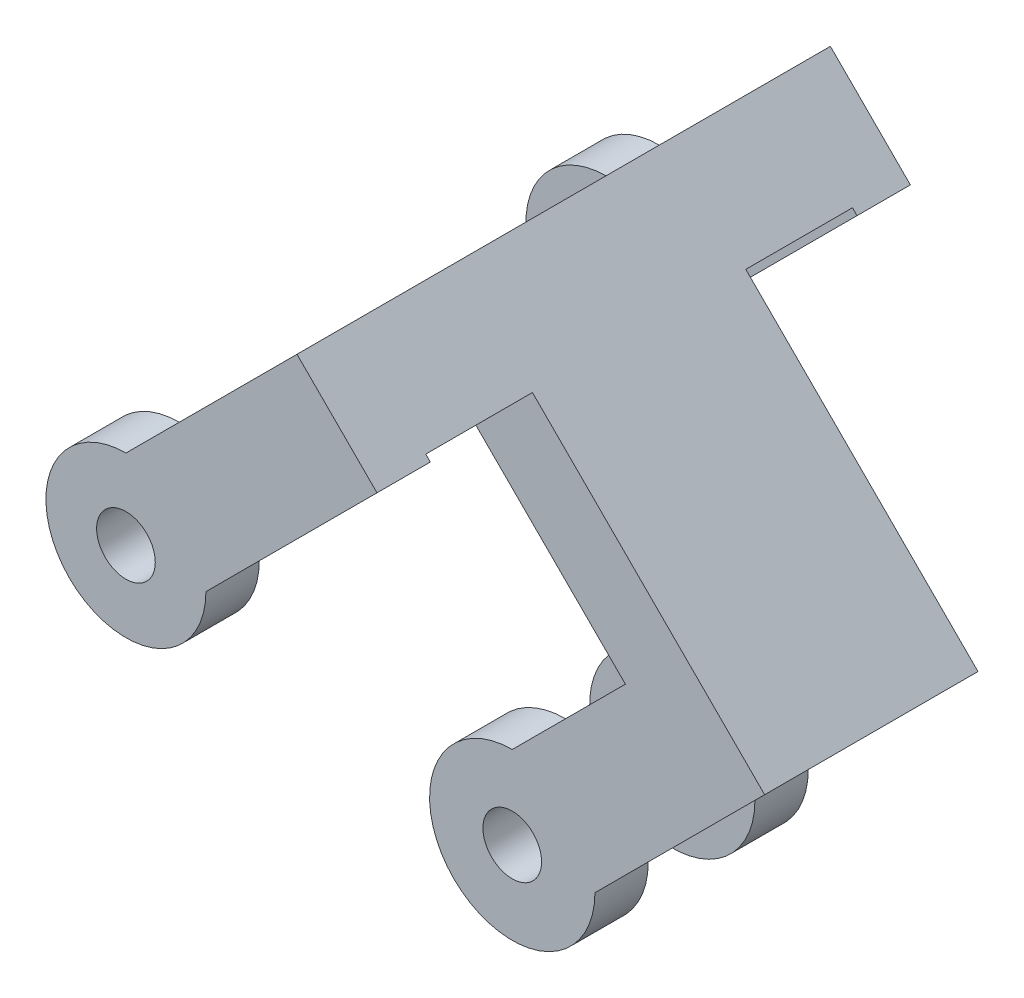
SolidWorks part; units mm, degrees
ref_plane "Front Plane" through (0, 0, 0) normal (0, 0, 1) x (1, 0, 0)
ref_plane "Top Plane" through (0, 0, 0) normal (0, 1, 0) x (1, 0, 0)
ref_plane "Right Plane" through (0, 0, 0) normal (1, 0, 0) x (0, 0, -1)
sketch "Sketch1" plane through (0, 0, 0) normal (0, 0, 1) x (1, 0, 0)
  circle A0 centre (-68.7868, 328.7868) radius 2.75 construction
  circle A1 centre (-68.7868, 328.7868) radius 2.75
  circle A2 centre (-68.7868, 328.7868) radius 7.75
  dimension "D1" = 5
extrude "Boss-Extrude1" add sketch "Sketch1" along normal blind 5
sketch "Sketch2" plane through (0, 0, -10) normal (0, 0, -1) x (-1, 0, 0)
  circle A0 centre (68.7868, 328.7868) radius 2.75 construction
  circle A1 centre (68.7868, 328.7868) radius 7.75
  circle A2 centre (68.7868, 328.7868) radius 7.75
  circle A3 centre (68.7868, 328.7868) radius 2.75
  dimension "D1" = 0
extrude "Boss-Extrude2" add sketch "Sketch2" along normal blind 5 separate body
sketch "Sketch3" plane through (0, 0, -15) normal (0, 0, -1) x (-1, 0, 0)
  line L0 (61.0368, 328.7868) -> (43.3591, 346.4645)
  line L1 (43.3591, 346.4645) -> (72.1973, 375.3027)
  line L2 (90, 357.5) -> (72.1973, 375.3027)
  line L3 (82.5, 350) -> (69.6471, 362.8529)
  line L4 (68.7868, 336.5368) -> (56.0589, 349.2647)
  line L5 (56.0589, 349.2647) -> (69.6471, 362.8529)
  circle A0 centre (68.7868, 328.7868) radius 7.75 construction
  circle A1 centre (90, 350) radius 2.75
  circle A2 centre (90, 350) radius 7.5
  circle M6 centre (68.7868, 328.7868) radius 7.75
  dimension "D3" = 15
  dimension "D1" = 25
  dimension "D2" = 18
extrude "Boss-Extrude4" add sketch "Sketch3" against normal blind 5 contours A2 A1 | A2 L2 L1 L0 L4 L5 L3 M6
sketch "Sketch4" plane through (0, 0, 0) normal (0, 0, 1) x (1, 0, 0)
  line L6 (-61.0368, 328.7868) -> (-43.3591, 346.4645)
  line L7 (-43.3591, 346.4645) -> (-72.1973, 375.3027)
  line L8 (-72.1973, 375.3027) -> (-90, 357.5)
  line L9 (-82.5, 350) -> (-69.6471, 362.8529)
  line L10 (-69.6471, 362.8529) -> (-56.0589, 349.2647)
  line L11 (-56.0589, 349.2647) -> (-68.7868, 336.5368)
  line L12 (-61.0368, 328.7868) -> (-43.3591, 346.4645)
  line L13 (-43.3591, 346.4645) -> (-72.1973, 375.3027)
  line L14 (-72.1973, 375.3027) -> (-90, 357.5)
  line L15 (-82.5, 350) -> (-69.6471, 362.8529)
  line L16 (-69.6471, 362.8529) -> (-56.0589, 349.2647)
  line L17 (-56.0589, 349.2647) -> (-68.7868, 336.5368)
  arc A2 (-68.7868, 336.5368) -> (-61.0368, 328.7868) centre (-68.7868, 328.7868) ccw
  arc A3 (-90, 357.5) -> (-82.5, 350) centre (-90, 350) ccw
  arc A4 (-68.7868, 336.5368) -> (-61.0368, 328.7868) centre (-68.7868, 328.7868) ccw
  arc A5 (-90, 357.5) -> (-82.5, 350) centre (-90, 350) ccw
  dimension "D1" = 0
extrude "Boss-Extrude5" add sketch "Sketch4" along normal blind 5
sketch "Sketch6" plane through (151.5527, 151.5527, 0) normal (0.7071, 0.7071, 0) x (0, 0, -1)
  line L1 (-5, 316.4303) -> (15, 316.4303)
  line L2 (-5, 316.4303) -> (-5, 275.6469)
  line L3 (-5, 275.6469) -> (15, 275.6469)
  line L4 (15, 316.4303) -> (15, 275.6469)
extrude "Boss-Extrude6" add sketch "Sketch6" against normal blind 10
sketch "Sketch7" plane through (0, 0, 5) normal (0, 0, 1) x (1, 0, 0)
  circle A0 centre (-68.7868, 328.7868) radius 2.75 construction
  circle A1 centre (-90, 350) radius 2.75 construction
  circle A2 centre (-68.7868, 328.7868) radius 2.75
  circle A3 centre (-90, 350) radius 2.75
extrude "Cut-Extrude1" cut sketch "Sketch7" against normal blind 10
sketch "Sketch9" plane through (0, 0, 5) normal (0, 0, 1) x (1, 0, 0)
  line L0 (-71.7684, 360.7316) -> (-64.6973, 367.8027)
  line L1 (-71.7684, 360.7316) -> (-79.2684, 368.2316)
  line L6 (-72.1973, 375.3027) -> (-90, 357.5)
  line L7 (-82.5, 350) -> (-71.7684, 360.7316)
  line L8 (-71.7684, 360.7316) -> (-58.1802, 347.1434)
  line L9 (-58.1802, 347.1434) -> (-68.7868, 336.5368)
  line L10 (-61.0368, 328.7868) -> (-43.3591, 346.4645)
  line L11 (-43.3591, 346.4645) -> (-72.1973, 375.3027)
  line L12 (-72.1973, 375.3027) -> (-90, 357.5)
  line L13 (-82.5, 350) -> (-71.7684, 360.7316)
  line L14 (-71.7684, 360.7316) -> (-58.1802, 347.1434)
  line L15 (-58.1802, 347.1434) -> (-68.7868, 336.5368)
  line L16 (-61.0368, 328.7868) -> (-43.3591, 346.4645)
  line L17 (-43.3591, 346.4645) -> (-72.1973, 375.3027)
  arc A2 (-90, 357.5) -> (-82.5, 350) centre (-90, 350) ccw
  arc A3 (-68.7868, 336.5368) -> (-61.0368, 328.7868) centre (-68.7868, 328.7868) ccw
  arc A4 (-90, 357.5) -> (-82.5, 350) centre (-90, 350) ccw
  arc A5 (-68.7868, 336.5368) -> (-61.0368, 328.7868) centre (-68.7868, 328.7868) ccw
  circle M10 centre (-90, 350) radius 2.75
  line M11 (-72.1973, 375.3027) -> (-90, 357.5)
  arc M12 (-90, 357.5) -> (-82.5, 350) centre (-90, 350) ccw
  line M13 (-82.5, 350) -> (-71.7684, 360.7316)
  dimension "D1" = 0
extrude "Cut-Extrude2" cut sketch "Sketch9" against normal through all contours L1 M13 M11 M12 M10
sketch "Sketch10" plane through (0, 0, 5) normal (0, 0, 1) x (1, 0, 0)
  line L0 (-65.1263, 368.2316) -> (-72.1973, 361.1605)
  line L5 (-72.1973, 375.3027) -> (-79.2684, 368.2316)
  line L6 (-79.2684, 368.2316) -> (-58.1802, 347.1434)
  line L7 (-58.1802, 347.1434) -> (-68.7868, 336.5368)
  line L8 (-61.0368, 328.7868) -> (-43.3591, 346.4645)
  line L9 (-43.3591, 346.4645) -> (-72.1973, 375.3027)
  line L10 (-72.1973, 375.3027) -> (-79.2684, 368.2316)
  line L11 (-79.2684, 368.2316) -> (-58.1802, 347.1434)
  line L12 (-58.1802, 347.1434) -> (-68.7868, 336.5368)
  line L13 (-61.0368, 328.7868) -> (-43.3591, 346.4645)
  line L14 (-43.3591, 346.4645) -> (-72.1973, 375.3027)
  arc A1 (-68.7868, 336.5368) -> (-61.0368, 328.7868) centre (-68.7868, 328.7868) ccw
  arc A2 (-68.7868, 336.5368) -> (-61.0368, 328.7868) centre (-68.7868, 328.7868) ccw
  line M7 (-72.1973, 375.3027) -> (-79.2684, 368.2316)
  line M8 (-79.2684, 368.2316) -> (-58.1802, 347.1434)
  line M12 (-43.3591, 346.4645) -> (-72.1973, 375.3027)
  dimension "D1" = 0
  dimension "D2" = 10
extrude "Boss-Extrude7" add sketch "Sketch10" along normal blind 15 contours L0 M12 M7 M8
sketch "Sketch11" plane through (0, 0, -15) normal (0, 0, -1) x (-1, 0, 0)
  line L4 (65.1263, 368.2316) -> (72.1973, 361.1605)
  line L5 (72.1973, 375.3027) -> (65.1263, 368.2316)
  line L6 (79.2684, 368.2316) -> (72.1973, 375.3027)
  line L7 (72.1973, 361.1605) -> (79.2684, 368.2316)
  line L8 (65.1263, 368.2316) -> (72.1973, 361.1605)
  line L9 (72.1973, 375.3027) -> (65.1263, 368.2316)
  line L10 (79.2684, 368.2316) -> (72.1973, 375.3027)
  line L11 (72.1973, 361.1605) -> (79.2684, 368.2316)
  dimension "D1" = 0
extrude "Boss-Extrude8" add sketch "Sketch11" along normal blind 15
sketch "Sketch12" plane through (0, 0, 20) normal (0, 0, 1) x (1, 0, 0)
  line L0 (-58.1802, 347.1434) -> (-51.1091, 354.2145)
  line L1 (-90, 357.5) -> (-79.2684, 368.2316)
  line L2 (-79.2684, 368.2316) -> (-50.4302, 339.3934)
  line L3 (-82.5, 350) -> (-64.2684, 368.2316)
  line L4 (-65.1263, 368.2316) -> (-64.6973, 367.8027)
  line L5 (-43.3591, 346.4645) -> (-65.1263, 368.2316)
  line L6 (-65.1263, 368.2316) -> (-72.1973, 361.1605)
  line L7 (-72.1973, 361.1605) -> (-58.1802, 347.1434)
  line L8 (-58.1802, 347.1434) -> (-68.7868, 336.5368)
  line L9 (-61.0368, 328.7868) -> (-43.3591, 346.4645)
  line L10 (-43.3591, 346.4645) -> (-51.1091, 354.2145)
  line L13 (-58.1802, 347.1434) -> (-68.7868, 336.5368)
  line L14 (-61.0368, 328.7868) -> (-43.3591, 346.4645)
  line L15 (-65.1263, 368.2316) -> (-43.3591, 346.4645) construction
  line L20 (-72.1973, 361.1605) -> (-65.1263, 368.2316)
  line L21 (-65.1263, 368.2316) -> (-72.1973, 375.3027)
  line L22 (-72.1973, 375.3027) -> (-79.2684, 368.2316)
  line L23 (-79.2684, 368.2316) -> (-72.1973, 361.1605)
  line L24 (-72.1973, 361.1605) -> (-65.1263, 368.2316)
  line L25 (-65.1263, 368.2316) -> (-72.1973, 375.3027)
  line L26 (-72.1973, 375.3027) -> (-79.2684, 368.2316)
  line L27 (-79.2684, 368.2316) -> (-72.1973, 361.1605)
  circle A0 centre (-68.7868, 328.7868) radius 2.75 construction
  arc A1 (-68.7868, 336.5368) -> (-61.0368, 328.7868) centre (-68.7868, 328.7868) ccw
  arc A2 (-68.7868, 336.5368) -> (-61.0368, 328.7868) centre (-68.7868, 328.7868) ccw
  circle A3 centre (-68.7868, 328.7868) radius 2.75
  circle A4 centre (-90, 350) radius 2.75
  circle A5 centre (-90, 350) radius 7.5
  line M14 (-72.1973, 361.1605) -> (-65.1263, 368.2316)
  line M17 (-79.2684, 368.2316) -> (-72.1973, 361.1605)
  dimension "D2" = 15
  dimension "D1" = 0
  dimension "D3" = 0
extrude "Boss-Extrude9" add sketch "Sketch12" against normal blind 5 contours A5 L3 L2 L1 M17 | A5 A4 | L4 L2 L3 M14
sketch "Sketch13" plane through (0, 0, -30) normal (0, 0, -1) x (-1, 0, 0)
  line L5 (90, 357.5) -> (79.2684, 368.2316)
  line L6 (79.2684, 368.2316) -> (72.1973, 361.1605)
  line L7 (72.1973, 361.1605) -> (65.1263, 368.2316)
  line L8 (65.1263, 368.2316) -> (64.6973, 367.8027)
  line L9 (64.6973, 367.8027) -> (82.5, 350)
  line L10 (90, 357.5) -> (79.2684, 368.2316)
  line L11 (79.2684, 368.2316) -> (72.1973, 361.1605)
  line L12 (72.1973, 361.1605) -> (65.1263, 368.2316)
  line L13 (65.1263, 368.2316) -> (64.6973, 367.8027)
  line L14 (64.6973, 367.8027) -> (82.5, 350)
  circle A0 centre (90, 350) radius 2.75 construction
  arc A1 (82.5, 350) -> (90, 357.5) centre (90, 350) ccw
  arc A2 (82.5, 350) -> (90, 357.5) centre (90, 350) ccw
  circle A3 centre (90, 350) radius 2.75
  dimension "D1" = 0
extrude "Boss-Extrude10" add sketch "Sketch13" against normal blind 5
sketch "Sketch14" plane through (151.5527, 151.5527, 0) normal (0.7071, 0.7071, 0) x (0, 0, -1)
  line L12 (-5, 275.6469) -> (15, 275.6469)
  line L13 (15, 275.6469) -> (15, 306.4303)
  line L14 (15, 306.4303) -> (25, 306.4303)
  line L15 (25, 306.4303) -> (25, 305.8237)
  line L16 (25, 305.8237) -> (30, 305.8237)
  line L17 (30, 305.8237) -> (30, 316.4303)
  line L18 (30, 316.4303) -> (-20, 316.4303)
  line L19 (-20, 316.4303) -> (-20, 305.8237)
  line L20 (-20, 305.8237) -> (-15, 305.8237)
  line L21 (-15, 305.8237) -> (-15, 306.4303)
  line L22 (-15, 306.4303) -> (-5, 306.4303)
  line L23 (-5, 306.4303) -> (-5, 275.6469)
  line L24 (-5, 275.6469) -> (15, 275.6469)
  line L25 (15, 275.6469) -> (15, 306.4303)
  line L26 (15, 306.4303) -> (25, 306.4303)
  line L27 (25, 306.4303) -> (25, 305.8237)
  line L28 (25, 305.8237) -> (30, 305.8237)
  line L29 (30, 305.8237) -> (30, 316.4303)
  line L30 (30, 316.4303) -> (-20, 316.4303)
  line L31 (-20, 316.4303) -> (-20, 305.8237)
  line L32 (-20, 305.8237) -> (-15, 305.8237)
  line L33 (-15, 305.8237) -> (-15, 306.4303)
  line L34 (-15, 306.4303) -> (-5, 306.4303)
  line L35 (-5, 306.4303) -> (-5, 275.6469)
  dimension "D1" = 0
extrude "Cut-Extrude3" cut sketch "Sketch14" against normal blind 5
sketch "Sketch15" plane through (148.0171, 148.0171, 0) normal (0.7071, 0.7071, 0) x (0, 0, -1)
  line L12 (-5, 306.4303) -> (-5, 275.6469)
  line L13 (-5, 275.6469) -> (15, 275.6469)
  line L14 (15, 275.6469) -> (15, 306.4303)
  line L15 (15, 306.4303) -> (25, 306.4303)
  line L16 (25, 306.4303) -> (25, 305.8237)
  line L17 (25, 305.8237) -> (30, 305.8237)
  line L18 (30, 305.8237) -> (30, 316.4303)
  line L19 (30, 316.4303) -> (-20, 316.4303)
  line L20 (-20, 316.4303) -> (-20, 305.8237)
  line L21 (-20, 305.8237) -> (-15, 305.8237)
  line L22 (-15, 305.8237) -> (-15, 306.4303)
  line L23 (-15, 306.4303) -> (-5, 306.4303)
  line L24 (-5, 306.4303) -> (-5, 275.6469)
  line L25 (-5, 275.6469) -> (15, 275.6469)
  line L26 (15, 275.6469) -> (15, 306.4303)
  line L27 (15, 306.4303) -> (25, 306.4303)
  line L28 (25, 306.4303) -> (25, 305.8237)
  line L29 (25, 305.8237) -> (30, 305.8237)
  line L30 (30, 305.8237) -> (30, 316.4303)
  line L31 (30, 316.4303) -> (-20, 316.4303)
  line L32 (-20, 316.4303) -> (-20, 305.8237)
  line L33 (-20, 305.8237) -> (-15, 305.8237)
  line L34 (-15, 305.8237) -> (-15, 306.4303)
  line L35 (-15, 306.4303) -> (-5, 306.4303)
  dimension "D1" = 0
extrude "Boss-Extrude11" add sketch "Sketch15" along normal blind 2.5
